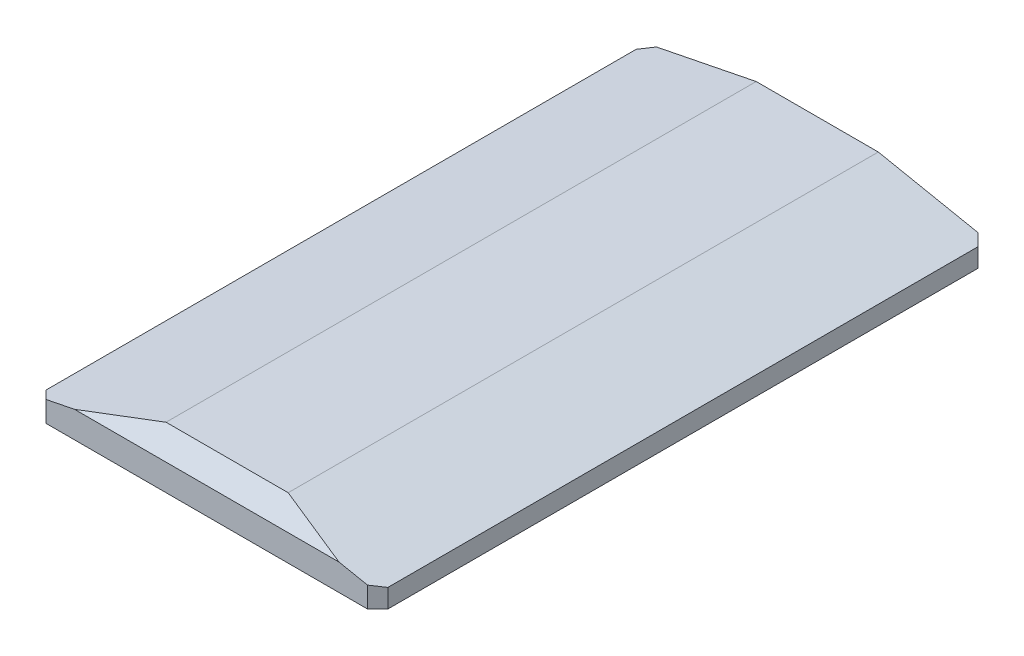
SolidWorks part; units mm, degrees
ref_plane "Спереди" through (0, 0, 0) normal (0, 0, 1) x (1, 0, 0)
ref_plane "Сверху" through (0, 0, 0) normal (0, 1, 0) x (1, 0, 0)
ref_plane "Справа" through (0, 0, 0) normal (1, 0, 0) x (0, 0, -1)
sketch "Эскиз1" plane through (0, 0, 0) normal (0, 0, 1) x (1, 0, 0)
  line L0 (-2.4393, 0.9) -> (2.4393, 0.9)
  line L11 (8.4, 0.9) -> (8.4, 1.8)
  line L32 (-8.4, 1.8) -> (-8.4, 0.9)
  line L33 (-8.4, 1.8) -> (-8.4, 1.82)
  line L34 (8.4, 1.8) -> (8.4, 1.82)
  line L35 (8.5, 1.8) -> (8.4, 1.82) construction
  line L36 (8.4, 0.9) -> (8.5, 0.9) construction
  line L37 (3, 2.9) -> (-3, 2.9)
  line L38 (-3, 2.9) -> (-8.5, 1.8)
  line L39 (-8.5, 1.8) -> (-8.5, 0.9)
  line L40 (-8.5, 0.9) -> (-2.4393, 0.9)
  line L41 (2.4393, 0.9) -> (8.5, 0.9)
  line L42 (8.5, 0.9) -> (8.5, 1.8)
  line L43 (8.5, 1.8) -> (3, 2.9)
  line L44 (3, 2.9) -> (-3, 2.9)
  line L45 (-3, 2.9) -> (-8.4, 1.82)
  line L46 (-8.5, 1.8) -> (-8.5, 0.9) construction
  line L47 (-8.4, 0.9) -> (-2.4393, 0.9)
  line L48 (2.4393, 0.9) -> (8.4, 0.9)
  line L49 (8.5, 0.9) -> (8.5, 1.8) construction
  line L50 (8.4, 1.82) -> (3, 2.9)
  line L51 (-8.4, 1.82) -> (-8.5, 1.8) construction
  line L52 (-8.5, 0.9) -> (-8.4, 0.9) construction
  arc A8 (2.4393, 0.9) -> (-2.4393, 0.9) centre (0, 0) ccw
  dimension "D2" = 0.1
  dimension "D1" = 0
extrude "Бобышка-Вытянуть1" add sketch "Эскиз1" against normal up to surface (3.5 mm away) and the other way up to surface (26.5 mm away)
sketch "Эскиз2" plane through (0, 0, 0) normal (1, 0, 0) x (0, 0, -1)
  line L0 (-26.5, 2.2) -> (-27.423, 1.5539) construction
  line L1 (-26.5, 2.2) -> (-27.423, 1.5539) construction
  line L2 (3.5, 2.9) -> (-26.5, 2.9) construction
  line L3 (-25.5, 2.9) -> (-26.5, 2.9)
  line L4 (-26.5, 2.2) -> (-25.5, 2.9)
  line L5 (-26.5, 1.82) -> (-26.5, 2.9) construction
  line L6 (-26.5, 2.2) -> (-26.5, 2.9)
  line L7 (-26.5, 1.82) -> (-26.5, 2.2) construction
  line L8 (3.5, 2.9) -> (-25.5, 2.9) construction
extrude "Вырез-Вытянуть1" cut sketch "Эскиз2" against normal through all both and the other way through all
sketch "Эскиз3" plane through (0, 0.9, 0) normal (0, -1, 0) x (1, 0, 0)
  line L0 (7.4, -2.5) -> (7.4, 25.5)
  line L1 (7.4, 25.5) -> (-7.4, 25.5)
  line L2 (-7.4, 25.5) -> (-7.4, -2.5)
  line L3 (-7.4, -2.5) -> (7.4, -2.5)
  line L4 (-8.4, 26.5) -> (-8.4, -3.5)
  line L5 (-8.4, -3.5) -> (8.4, -3.5)
  line L6 (8.4, -3.5) -> (8.4, 26.5)
  line L7 (8.4, 26.5) -> (-8.4, 26.5)
  line L8 (-8.4, 26.5) -> (-8.4, -3.5)
  line L9 (-8.4, -3.5) -> (8.4, -3.5)
  line L10 (8.4, -3.5) -> (8.4, 26.5)
  line L11 (8.4, 26.5) -> (-8.4, 26.5)
  dimension "D1" = 0
  dimension "D2" = 1
extrude "Вырез-Вытянуть2" cut sketch "Эскиз3" against normal blind 1 contours L2 L3 L0 L1
chamfer "Фаска1" distance 0.5 angle 45 4 edges at (0, 1.9, 25.5) (7.4, 1.9, 11.5) (0, 1.9, -2.5) (-7.4, 1.9, 11.5)
chamfer "Фаска2" distance 0.5 angle 45 4 edges at (-8.4, 1.36, -3.5) (8.4, 1.36, -3.5) (8.4, 1.36, 26.5) (-8.4, 1.36, 26.5)
